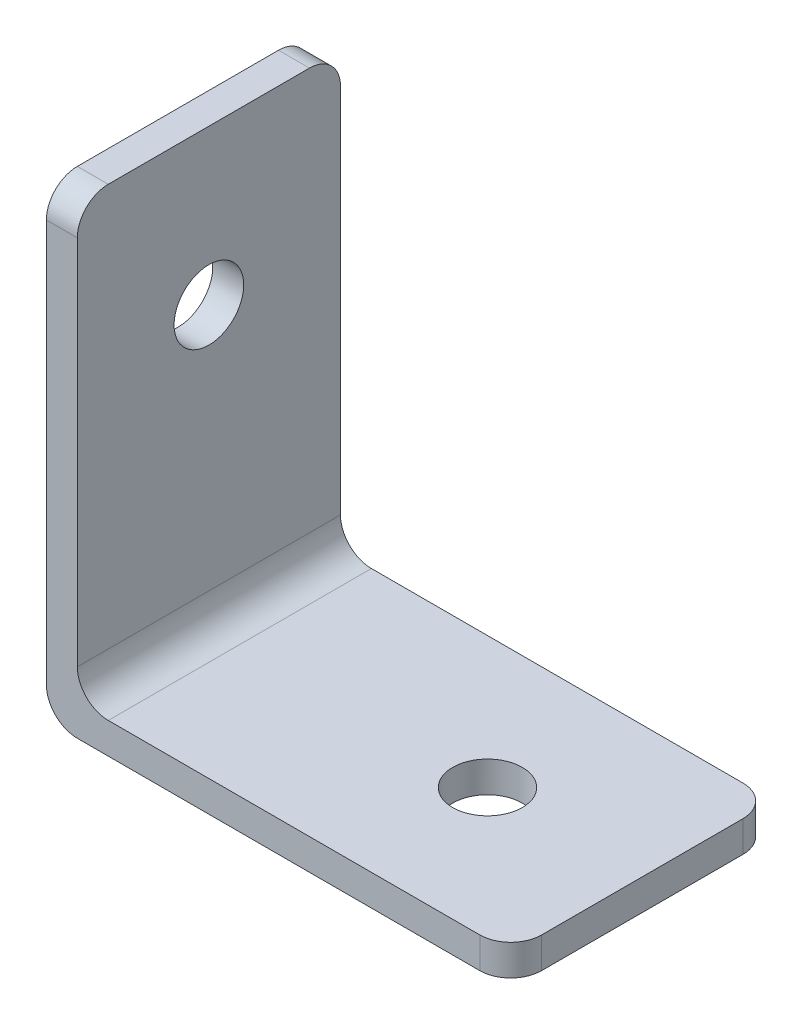
SolidWorks part; units mm, degrees
ref_plane "Front Plane" through (0, 0, 0) normal (0, 0, 1) x (1, 0, 0)
ref_plane "Top Plane" through (0, 0, 0) normal (0, 1, 0) x (1, 0, 0)
ref_plane "Right Plane" through (0, 0, 0) normal (1, 0, 0) x (0, 0, -1)
sketch "Sketch1" plane through (0, 0, 0) normal (0, 0, 1) x (1, 0, 0)
  line L0 (0, 30) -> (0, 0)
  line L1 (0, 0) -> (30, 0)
  dimension "D1" = 30
  dimension "D2" = 30
extrude "Extrude-Thin1" add sketch "Sketch1" along normal blind 17 thin thin type one direction reverse wall 2
fillet "Fillet1" radius 2 4 edges at (30, 1, 17) (30, 1, 0) (1, 30, 17) (1, 30, 0)
fillet "Fillet2" radius 2 2 edges at (0, 0, 8.5) (2, 2, 8.5)
sketch "Sketch2" plane through (0, 0, 0) normal (-1, 0, 0) x (0, 0, 1)
  line L0 (15, 30) -> (2, 30) construction
  line L1 (15, 30) -> (2, 30) construction
  line L2 (17, 28) -> (17, 2) construction
  circle A0 centre (8.5, 20) radius 2.25
  point P2 (8.5, 30)
  dimension "D1" = 10
  dimension "D2" = 8.5
  dimension "D3" = 4.5
extrude "Cut-Extrude1" cut sketch "Sketch2" against normal blind 10
sketch "Sketch4" plane through (0, 0, 0) normal (0, -1, 0) x (1, 0, 0)
  line L0 (2, 17) -> (28, 17) construction
  line L1 (30, 15) -> (30, 2) construction
  circle A0 centre (20, 8.5) radius 2.25
  dimension "D1" = 4.5
  dimension "D2" = 8.5
  dimension "D3" = 10
extrude "Cut-Extrude2" cut sketch "Sketch4" against normal blind 10
